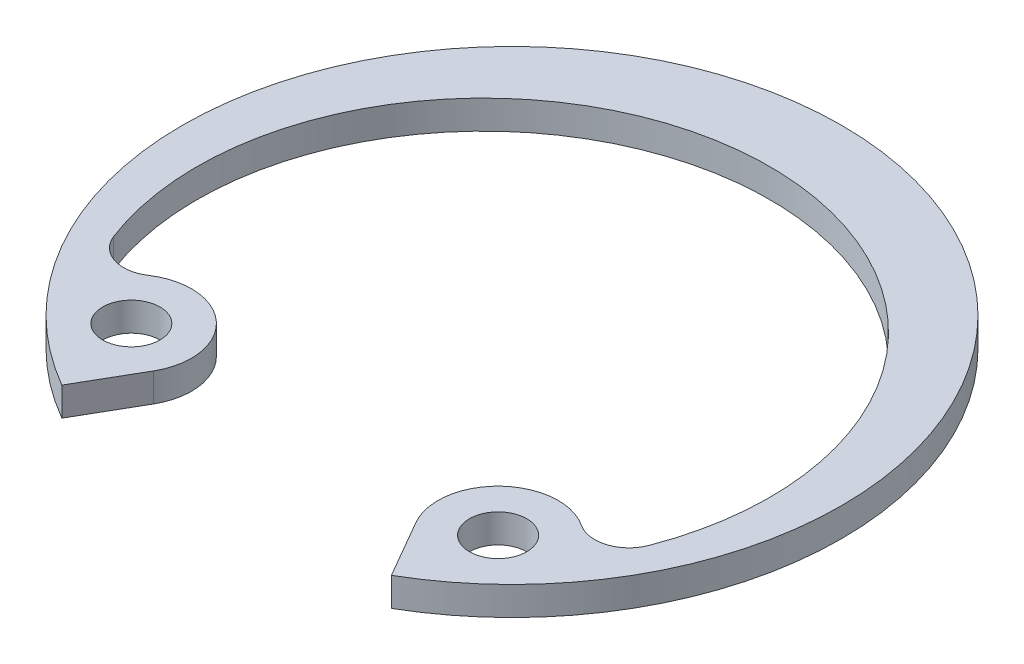
SolidWorks part; units mm, degrees
material "合金钢"
ref_plane "前视基准面" through (0, 0, 0) normal (0, 0, 1) x (1, 0, 0)
ref_plane "上视基准面" through (0, 0, 0) normal (0, 1, 0) x (1, 0, 0)
ref_plane "右视基准面" through (0, 0, 0) normal (1, 0, 0) x (0, 0, -1)
other "Configuration Table"
sketch "草图1" plane through (0, 0, 0) normal (0, 1, 0) x (1, 0, 0)
  line L0 (-5.75, -9.9593) -> (-4.5812, -7.9349)
  line L1 (4.5812, -7.9349) -> (5.75, -9.9593)
  arc A0 (-4.5812, -7.9349) -> (-7.558, -5.1331) centre (-6.3999, -6.8849) ccw
  arc A1 (-7.558, -5.1331) -> (-9.3411, -4.5597) centre (-8.2198, -4.1321) cw
  arc A2 (-9.3411, -4.5597) -> (9.3411, -4.5597) centre (0, -0.9973) cw
  arc A3 (9.3411, -4.5597) -> (7.558, -5.1331) centre (8.2198, -4.1321) cw
  arc A4 (7.558, -5.1331) -> (4.5812, -7.9349) centre (6.3999, -6.8849) ccw
  arc A5 (5.75, -9.9593) -> (-5.75, -9.9593) centre (0, 0) ccw
  circle A6 centre (-6.3999, -6.8849) radius 1
  circle A7 centre (6.3999, -6.8849) radius 1
  circle A8 centre (0, 0) radius 9.4 construction
  circle A9 centre (0, 0) radius 7.3 construction
  circle A10 centre (0, 0) radius 10.4 construction
  point P14 (0, 11.5)
  point P19 (0, 9)
  dimension "d2" = 23
  dimension "da" = 14.6
  dimension "d6" = 18.8
  dimension "d5" = 2
  dimension "r1" = 1.2
  dimension "D1" = 60
  dimension "b" = 2.5
extrude "凸台-拉伸1" add sketch "草图1" along normal blind 1
equation "\"a\"= 4.2mm"
equation "\"da@草图1\" = \"d2@草图1\" - 2 * \"a\""
equation "\"d6@草图1\" = 0.5 * \"d2@草图1\" + 0.5 * \"da@草图1\""
